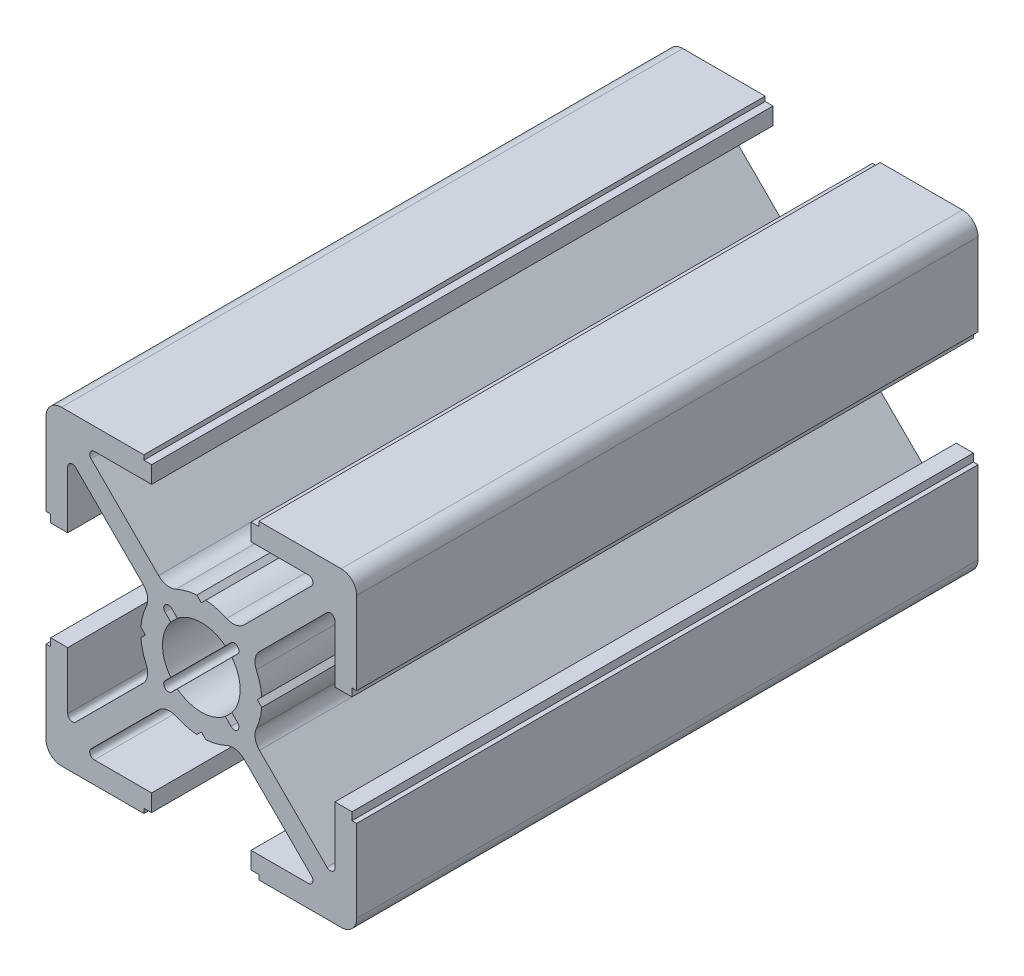
SolidWorks part; units mm, degrees
material "6063-O"
ref_plane "Ön Düzlem" through (0, 0, 0) normal (0, 0, 1) x (1, 0, 0)
ref_plane "Üst Düzlem" through (0, 0, 0) normal (0, 1, 0) x (1, 0, 0)
ref_plane "Sağ Düzlem" through (0, 0, 0) normal (1, 0, 0) x (0, 0, -1)
sketch "Çizim1" plane through (0, 0, 0) normal (0, 0, 1) x (1, 0, 0)
  line L0 (-10, -3.2) -> (-8.6, -3.2)
  line L1 (-10, -10) -> (10, -10) construction
  line L2 (-10, -10) -> (-10, 10) construction
  line L3 (-10, 10) -> (10, 10) construction
  line L4 (10, -10) -> (10, 10) construction
  line L5 (0, 10) -> (0, -10) construction
  line L6 (-10, 0) -> (10, 0) construction
  line L7 (-3.2, 9.7) -> (-3.2, 8.6)
  line L8 (-10, 3.2) -> (-8.6, 3.2)
  line L9 (3.2, 9.7) -> (3.2, 8.6)
  line L10 (-10, -10) -> (10, 10) construction
  line L11 (-10, 10) -> (10, -10) construction
  line L12 (-8.4103, -9.4002) -> (8.9459, 7.956)
  line L13 (-9.5475, 8.5575) -> (8.5575, -9.5475)
  line L14 (-9.5475, -8.5575) -> (8.1743, 9.1642)
  line L15 (-8.5764, 9.5663) -> (9.1804, -8.1905)
  line L16 (-8.6, 8.6) -> (-3.2, 8.6)
  line L17 (8.6, -8.6) -> (8.6, -3.2)
  line L18 (-8.6, -8.6) -> (-3.2, -8.6)
  line L19 (-8.6, -8.6) -> (-8.6, -3.2)
  line L20 (-10.495, -9.505) -> (9.505, 10.495) construction
  line L21 (-9.505, -10.495) -> (10.495, 9.505) construction
  line L22 (-9.505, 10.495) -> (10.495, -9.505) construction
  line L23 (-10.495, 9.505) -> (9.505, -10.495) construction
  line L24 (3.7, 10) -> (10, 10)
  line L25 (10, 10) -> (10, 3.2)
  line L26 (10, -3.2) -> (10, -10)
  line L27 (10, -10) -> (3.2, -10)
  line L28 (-3.2, -10) -> (-10, -10)
  line L29 (-10, -10) -> (-10, -3.2)
  line L30 (-10, 3.2) -> (-10, 10)
  line L31 (-10, 10) -> (-3.7, 10)
  line L32 (-3.2, 9.7) -> (-3.7, 9.7)
  line L33 (-3.7, 9.7) -> (-3.7, 10)
  line L34 (8.6, 3.2) -> (8.6, 8.6)
  line L35 (8.6, -8.6) -> (8.6, 8.6) construction
  line L36 (-8.6, 3.2) -> (-8.6, 8.6)
  line L37 (-8.6, -8.6) -> (-8.6, 8.6) construction
  line L38 (3.2, 8.6) -> (8.6, 8.6)
  line L39 (-8.6, 8.6) -> (8.6, 8.6) construction
  line L40 (-3.2, 10) -> (-3.2, -10) construction
  line L41 (9.7, 3.2) -> (9.7, 3.7)
  line L42 (9.7, 3.7) -> (10, 3.7)
  line L43 (-10, 3.2) -> (10, 3.2) construction
  line L44 (9.7, -3.7) -> (10, -3.7)
  line L45 (3.2, 10) -> (3.2, -10) construction
  line L46 (8.6, 3.2) -> (10, 3.2)
  line L47 (8.6, -3.2) -> (10, -3.2)
  line L48 (-10, -3.2) -> (10, -3.2) construction
  line L49 (3.2, -8.6) -> (3.2, -10)
  line L50 (-3.2, -8.6) -> (-3.2, -10)
  line L51 (3.2, -8.6) -> (8.6, -8.6)
  line L52 (-8.6, -8.6) -> (8.6, -8.6) construction
  line L53 (3.7, 9.7) -> (3.7, 10)
  line L54 (3.2, 9.7) -> (3.7, 9.7)
  line L55 (9.7, -3.2) -> (9.7, -3.7)
  line L56 (3.2, -9.7) -> (3.7, -9.7)
  line L57 (3.7, -9.7) -> (3.7, -10)
  line L58 (-3.7, -9.7) -> (-3.7, -10)
  line L59 (-3.2, -9.7) -> (-3.7, -9.7)
  line L60 (-9.7, -3.2) -> (-9.7, -3.7)
  line L61 (-9.7, -3.7) -> (-10, -3.7)
  line L62 (-9.7, 3.7) -> (-10, 3.7)
  line L63 (-9.7, 3.2) -> (-9.7, 3.7)
  line L64 (-0.3719, 3.9719) -> (0, 3.6)
  line L65 (0, 3.6) -> (0.3743, 3.9743)
  line L66 (3.9719, 0.3719) -> (3.6, 0)
  line L67 (3.6, 0) -> (3.9743, -0.3743)
  line L68 (0.3719, -3.9719) -> (0, -3.6)
  line L69 (0, -3.6) -> (-0.3743, -3.9743)
  line L70 (-3.9719, -0.3719) -> (-3.6, 0)
  line L71 (-3.6, 0) -> (-3.9743, 0.3743)
  line L72 (1.9092, 2.3335) -> (1.5429, 1.9671)
  line L73 (2.3335, 1.9092) -> (1.9671, 1.5429)
  line L74 (2.3335, -1.9092) -> (1.9671, -1.5429)
  line L75 (1.9092, -2.3335) -> (1.5429, -1.9671)
  line L76 (-1.9092, -2.3335) -> (-1.5429, -1.9671)
  line L77 (-2.3335, -1.9092) -> (-1.9671, -1.5429)
  line L78 (-2.3335, 1.9092) -> (-1.9671, 1.5429)
  line L79 (-1.9092, 2.3335) -> (-1.5429, 1.9671)
  circle A0 centre (0, 0) radius 2.5
  circle A1 centre (0, 0) radius 3.9
  circle A2 centre (2.1213, 2.1213) radius 0.3
  circle A3 centre (2.1213, -2.1213) radius 0.3
  circle A4 centre (-2.1213, -2.1213) radius 0.3
  circle A5 centre (-2.1213, 2.1213) radius 0.3
  point P0 (0, 0)
  point P17 (0, 0)
  point P18 (0, 0)
  point P72 (0, 0)
  point P91 (0, 0)
  point P116 (0, 0)
  dimension "D11" = 5
  dimension "D12" = 7.8
  dimension "D15" = 0.6
  dimension "D1" = 20
  dimension "D2" = 3.2
  dimension "D4" = 0.7
  dimension "D5" = 0.7
  dimension "D6" = 1.4
  dimension "D7" = 0.5
  dimension "D8" = 0.3
  dimension "D9" = 0.5
  dimension "D13" = 0.3
  dimension "D16" = 0.5
  dimension "D17" = 4
  dimension "D3" = 3.2
  dimension "D10" = 4
  dimension "D14" = 4
extrude "Yükseklik-Ekstrüzyon1" add sketch "Çizim1" along normal blind 40
fillet "Radyus1" radius 1 8 edges at (-3.2079, 2.218, 20) (2.218, -3.2079, 20) (-3.2079, -2.218, 20) (2.218, 3.2079, 20) (-2.218, -3.2079, 20) (3.2079, 2.218, 20) (-2.218, 3.2079, 20) (3.2079, -2.218, 20)
fillet "Radyus2" radius 0.3 8 edges at (8.6, -7.6101, 20) (7.6101, -8.6, 20) (-7.6101, -8.6, 20) (-8.6, -7.6101, 20) (8.6, 7.6101, 20) (7.6101, 8.6, 20) (-7.6101, 8.6, 20) (-8.6, 7.6101, 20)
fillet "Radyus3" radius 1 4 edges at (-10, -10, 20) (-10, 10, 20) (10, -10, 20) (10, 10, 20)
